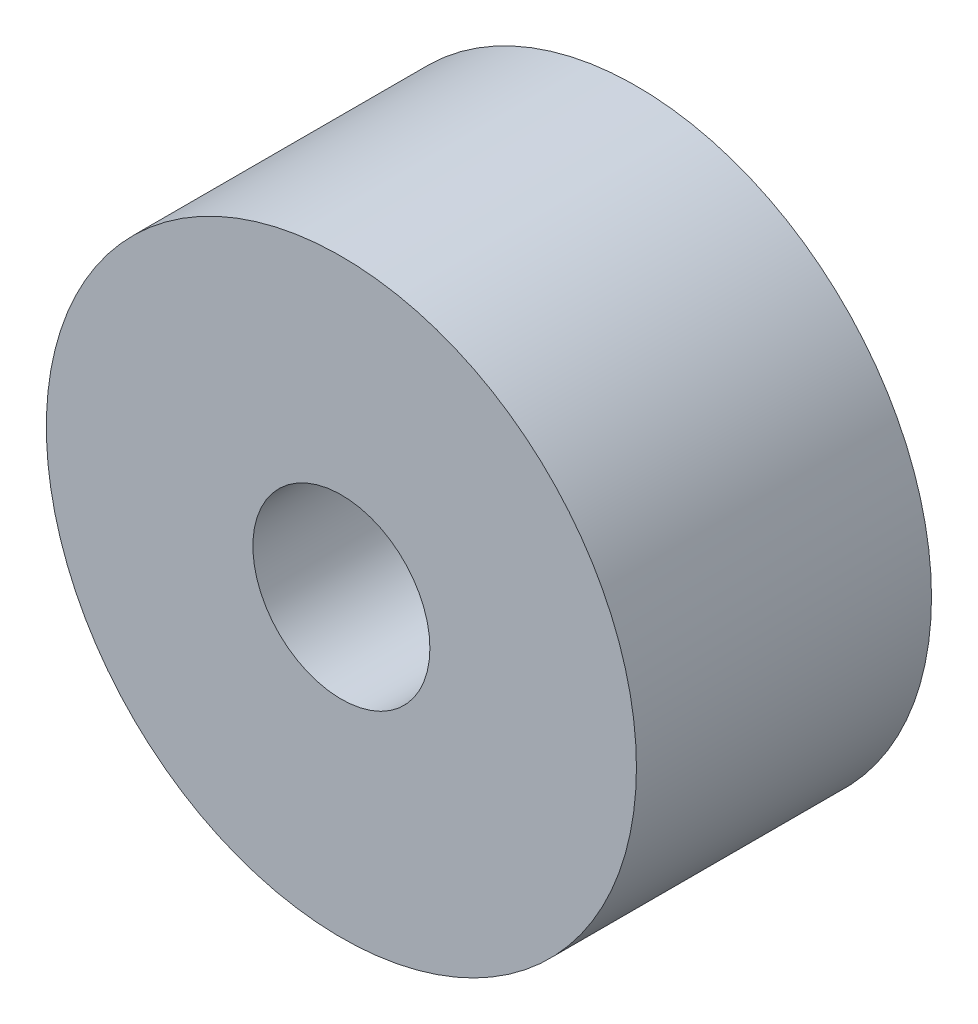
SolidWorks part; units mm, degrees
material "PLA"
ref_plane "前视基准面" through (0, 0, 0) normal (0, 0, 1) x (1, 0, 0)
ref_plane "上视基准面" through (0, 0, 0) normal (0, 1, 0) x (1, 0, 0)
ref_plane "右视基准面" through (0, 0, 0) normal (1, 0, 0) x (0, 0, -1)
sketch "草图1" plane through (0, 0, 0) normal (0, 0, 1) x (1, 0, 0)
  circle A0 centre (0, 0) radius 1.5
  circle A1 centre (0, 0) radius 5
  dimension "D1" = 3
  dimension "D2" = 10
extrude "凸台-拉伸1" add sketch "草图1" along normal blind 5
